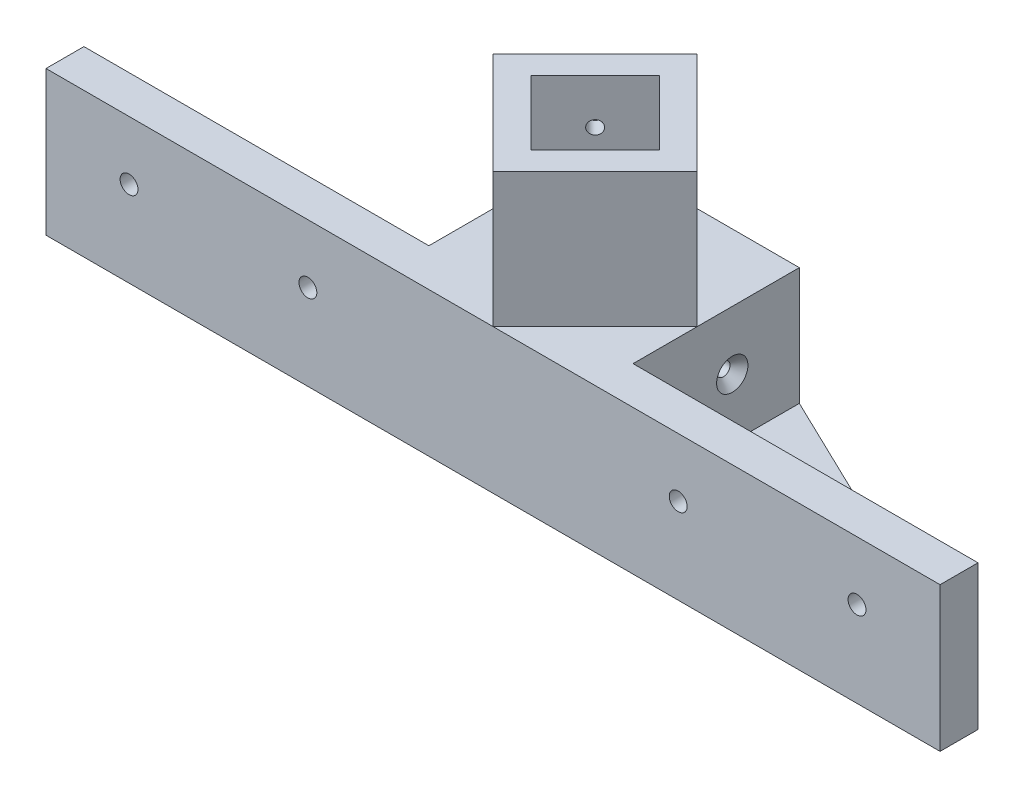
SolidWorks part; units mm, degrees
ref_plane "Plan de face" through (0, 0, 0) normal (0, 0, 1) x (1, 0, 0)
ref_plane "Plan de dessus" through (0, 0, 0) normal (0, 1, 0) x (1, 0, 0)
ref_plane "Plan de droite" through (0, 0, 0) normal (1, 0, 0) x (0, 0, -1)
sketch "Esquisse1" plane through (0, 0, 0) normal (0, 1, 0) x (1, 0, 0)
  line L0 (0, 0) -> (100, 0)
  line L1 (100, 0) -> (100, 8.4853)
  line L2 (100, 8.4853) -> (22.8395, 8.4853)
  line L3 (22.8395, 8.4853) -> (22.8395, 45.6791)
  line L4 (22.8395, 45.6791) -> (0, 45.6791)
  line L5 (0, 45.6791) -> (0, 0)
  line L6 (22.8395, 8.4853) -> (0, 8.4853) construction
  line L7 (0, 8.4853) -> (14.3543, 22.8395) construction
  line L8 (14.3543, 22.8395) -> (0, 37.1938) construction
  line L9 (0, 0) -> (22.8395, 22.8395) construction
  line L10 (22.8395, 22.8395) -> (0, 45.6791) construction
  line L11 (22.8395, 45.6791) -> (100, 8.4853)
  dimension "D1" = 20.3
  dimension "D2" = 6
  dimension "D3" = 6
  dimension "D4" = 100
extrude "Boss.-Extru.1" add sketch "Esquisse1" along normal blind 6 contours L11 L3 L2 | L4 L5 L0 L1 L2 L3
sketch "Esquisse2" plane through (0, 6, 0) normal (0, 1, 0) x (1, 0, 0)
  line L0 (22.8395, 45.6791) -> (10.15, 45.6791)
  line L4 (10.15, 45.6791) -> (10.15, 6)
  line L5 (10.15, 6) -> (0, 6)
  line L7 (0, 6) -> (0, 0)
  line L8 (0, 0) -> (100, 0)
  line L9 (100, 0) -> (100, 8.4853)
  line L10 (22.8395, 45.6791) -> (0, 45.6791) construction
  line L11 (100, 0) -> (100, 8.4853) construction
  line L12 (0, 0) -> (100, 0) construction
  line L13 (0, 45.6791) -> (0, 0) construction
  line L14 (100, 8.4853) -> (22.8395, 8.4853)
  line L15 (22.8395, 45.6791) -> (22.8395, 8.4853)
  dimension "D1" = 6
  dimension "D2" = 10.15
extrude "Boss.-Extru.2" add sketch "Esquisse2" along normal blind 20.3
sketch "Esquisse3" plane through (0, 26.3, 0) normal (0, 1, 0) x (1, 0, 0)
  line L0 (22.8395, 45.6791) -> (0, 45.6791)
  line L1 (0, 45.6791) -> (0, 0)
  line L2 (0, 0) -> (100, 0)
  line L3 (100, 0) -> (100, 8.4853)
  line L4 (100, 8.4853) -> (22.8395, 8.4853)
  line L5 (22.8395, 8.4853) -> (22.8395, 45.6791)
extrude "Boss.-Extru.3" add sketch "Esquisse3" along normal blind 6
sketch "Esquisse4" plane through (0, 32.3, 0) normal (0, 1, 0) x (1, 0, 0)
  line L0 (0, 0) -> (22.8395, 22.8395)
  line L1 (22.8395, 8.4853) -> (22.8395, 45.6791) construction
  line L2 (22.8395, 22.8395) -> (0, 45.6791)
  line L3 (0, 45.6791) -> (0, 37.1938)
  line L4 (0, 45.6791) -> (0, 0) construction
  line L5 (0, 37.1938) -> (14.3543, 22.8395)
  line L6 (14.3543, 22.8395) -> (0, 8.4853)
  line L7 (0, 8.4853) -> (0, 0)
  dimension "D1" = 6
extrude "Boss.-Extru.4" add sketch "Esquisse4" along normal blind 30
sketch "Esquisse5" plane through (22.8395, 0, -22.8395) normal (0.7071, 0, -0.7071) x (-0.7071, 0, -0.7071)
  line L0 (16.15, 62.3) -> (16.15, 32.3) construction
  line L1 (0, 62.3) -> (32.3, 62.3) construction
  line L2 (0, 32.3) -> (32.3, 32.3) construction
  circle A0 centre (16.15, 52.3) radius 1.5
  dimension "D2" = 3
  dimension "D1" = 10
extrude "Enlèv. mat.-Extru.1" cut sketch "Esquisse5" against normal blind 30
sketch "Esquisse6" plane through (22.8395, 0, 0) normal (1, 0, 0) x (0, 0, -1)
  line L0 (8.4853, 19.15) -> (45.6791, 19.15) construction
  line L1 (8.4853, 32.3) -> (8.4853, 6) construction
  line L2 (45.6791, 32.3) -> (45.6791, 6) construction
  circle A0 centre (30.6791, 19.15) radius 1.5
  dimension "D2" = 3
  dimension "D1" = 15
extrude "Enlèv. mat.-Extru.2" cut sketch "Esquisse6" against normal blind 30
sketch "Esquisse7" plane through (0, 0, -8.4853) normal (0, 0, -1) x (-1, 0, 0)
  line L0 (-100, 19.15) -> (-22.8395, 19.15) construction
  line L1 (-100, 32.3) -> (-100, 6) construction
  line L2 (-22.8395, 32.3) -> (-22.8395, 6) construction
  line L3 (-41.4198, 17.15) -> (-81.4198, 17.15) construction
  line L4 (-61.4198, 17.15) -> (-61.4198, 19.15) construction
  circle A0 centre (-41.4198, 19.15) radius 2
  circle A1 centre (-81.4198, 19.15) radius 2
  dimension "D1" = 4
  dimension "D2" = 40
extrude "Enlèv. mat.-Extru.3" cut sketch "Esquisse7" against normal blind 30
chamfer "Chanfrein1" distance 2 angle 45 4 edges at (22.8395, 19.15, -32.1791) (10.3591, 52.3, -35.32) (39.4198, 19.15, -8.4853) (79.4198, 19.15, -8.4853)
mirror "Symétrie1" about plane through (0, 6, 0) normal (1, 0, 0) of bodies 107
sketch "Esquisse9" [suppressed] plane through (0, 32, 0) normal (0, 1, 0) x (1, 0, 0)
  line L0 (-100, 0) -> (-100, 45.6791)
  line L1 (-100, 45.6791) -> (-22.8395, 45.6791)
  line L2 (-22.8395, 45.6791) -> (-22.8395, 0)
  line L3 (0, 0) -> (-100, 0) construction
  line L4 (-22.8395, 0) -> (-100, 0)
  line L5 (22.8395, 45.6791) -> (100, 45.6791)
  line L6 (100, 45.6791) -> (100, 0)
  line L7 (100, 0) -> (22.8395, 0)
  line L8 (0, 0) -> (100, 0) construction
  line L9 (22.8395, 0) -> (22.8395, 45.6791)
extrude "Enlèv. mat.-Extru.4" [suppressed] cut sketch "Esquisse9" against normal through all
